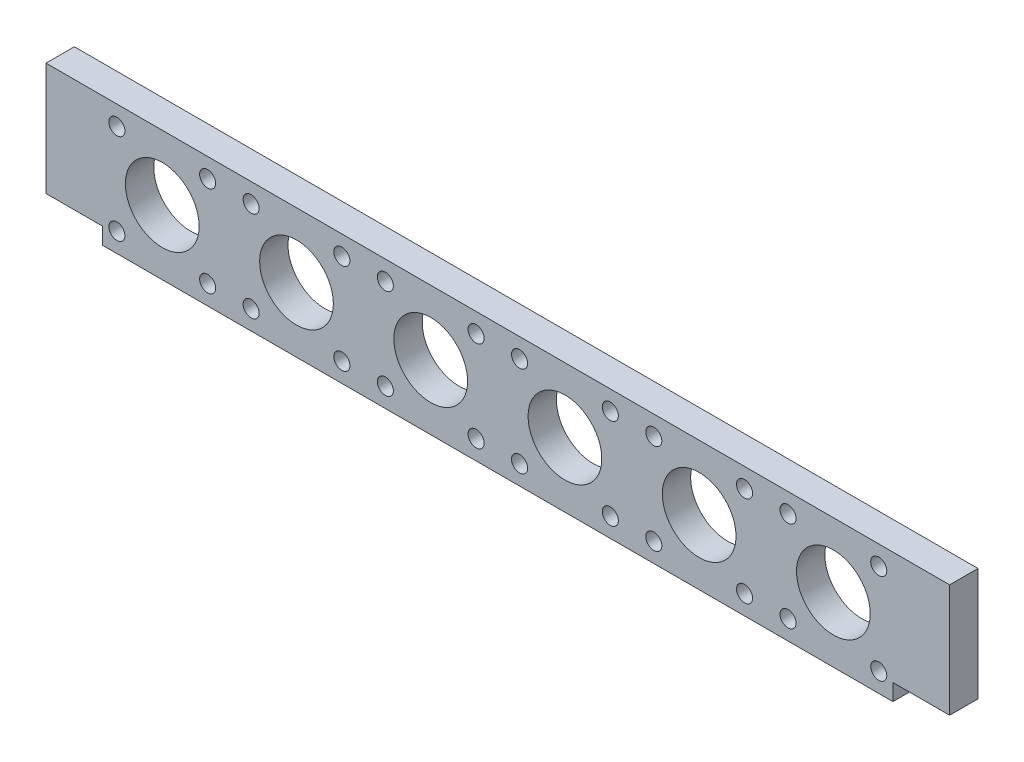
SolidWorks part; units mm, degrees
ref_plane "Front" through (0, 0, 0) normal (0, 0, 1) x (1, 0, 0)
ref_plane "Top" through (0, 0, 0) normal (0, 1, 0) x (1, 0, 0)
ref_plane "Right" through (0, 0, 0) normal (1, 0, 0) x (0, 0, -1)
sketch "Esquisse1" plane through (0, 0, 0) normal (0, 0, 1) x (1, 0, 0)
  line L1 (0, 0) -> (478, 0)
  line L2 (0, 0) -> (0, 68.5)
  line L3 (0, 68.5) -> (478, 68.5)
  line L4 (478, 0) -> (478, 68.5)
  dimension "D1" = 68.5
  dimension "D2" = 478
extrude "Boss.-Extru.1" add sketch "Esquisse1" along normal blind 15
sketch "Esquisse2" plane through (0, 0, 15) normal (0, 0, 1) x (1, 0, 0)
  line L0 (239, 0) -> (239, 68.5) construction
  line L1 (0, 0) -> (478, 0) construction
  line L2 (478, 68.5) -> (0, 68.5) construction
  line L3 (203.5, 68.5) -> (203.5, 34.25) construction
  line L4 (203.5, 34.25) -> (239, 34.25) construction
  line L5 (168, 68.5) -> (168, 0) construction
  line L6 (132.5, 68.5) -> (132.5, 34.25) construction
  line L7 (97, 68.5) -> (97, 0) construction
  line L8 (61.5, 68.5) -> (61.5, 34.25) construction
  line L9 (416.5, 68.5) -> (416.5, 34.25) construction
  line L10 (381, 68.5) -> (381, 0) construction
  line L11 (345.5, 68.5) -> (345.5, 34.25) construction
  line L12 (310, 68.5) -> (310, 0) construction
  line L13 (274.5, 68.5) -> (274.5, 34.25) construction
  circle A0 centre (227.5, 58.25) radius 4.25
  circle A1 centre (227.5, 10.25) radius 4.25
  circle A2 centre (179.5, 10.25) radius 4.25
  circle A3 centre (179.5, 58.25) radius 4.25
  circle A4 centre (156.5, 58.25) radius 4.25
  circle A5 centre (156.5, 10.25) radius 4.25
  circle A6 centre (108.5, 10.25) radius 4.25
  circle A7 centre (108.5, 58.25) radius 4.25
  circle A8 centre (85.5, 58.25) radius 4.25
  circle A9 centre (85.5, 10.25) radius 4.25
  circle A10 centre (37.5, 10.25) radius 4.25
  circle A11 centre (37.5, 58.25) radius 4.25
  circle A12 centre (440.5, 58.25) radius 4.25
  circle A13 centre (440.5, 10.25) radius 4.25
  circle A14 centre (392.5, 10.25) radius 4.25
  circle A15 centre (392.5, 58.25) radius 4.25
  circle A16 centre (369.5, 58.25) radius 4.25
  circle A17 centre (369.5, 10.25) radius 4.25
  circle A18 centre (321.5, 10.25) radius 4.25
  circle A19 centre (321.5, 58.25) radius 4.25
  circle A20 centre (298.5, 58.25) radius 4.25
  circle A21 centre (298.5, 10.25) radius 4.25
  circle A22 centre (250.5, 10.25) radius 4.25
  circle A23 centre (250.5, 58.25) radius 4.25
  dimension "D1" = 48
  dimension "D2" = 48
  dimension "D3" = 8.5
  dimension "D4" = 71
  dimension "D5" = 71
  dimension "D6" = 71
extrude "Enlèv. mat.-Extru.1" cut sketch "Esquisse2" against normal through all both and the other way through all
sketch "Esquisse3" plane through (0, 0, 15) normal (0, 0, 1) x (1, 0, 0)
  line L0 (179.5, 10.25) -> (227.5, 58.25) construction
  line L1 (108.5, 10.25) -> (156.5, 58.25) construction
  line L2 (37.5, 10.25) -> (85.5, 58.25) construction
  line L3 (239, 0) -> (239, 68.5) construction
  line L4 (0, 0) -> (478, 0) construction
  line L5 (478, 68.5) -> (0, 68.5) construction
  line L6 (440.5, 10.25) -> (392.5, 58.25) construction
  line L7 (369.5, 10.25) -> (321.5, 58.25) construction
  line L8 (298.5, 10.25) -> (250.5, 58.25) construction
  circle A0 centre (203.5, 34.25) radius 19.5
  circle A1 centre (132.5, 34.25) radius 19.5
  circle A2 centre (61.5, 34.25) radius 19.5
  circle A3 centre (416.5, 34.25) radius 19.5
  circle A4 centre (345.5, 34.25) radius 19.5
  circle A5 centre (274.5, 34.25) radius 19.5
  dimension "D1" = 39
extrude "Enlèv. mat.-Extru.2" cut sketch "Esquisse3" against normal through all both and the other way through all
sketch "Esquisse4" plane through (0, 0, 15) normal (0, 0, 1) x (1, 0, 0)
  line L0 (239, 0) -> (239, 68.5) construction
  line L1 (0, 0) -> (30, 0)
  line L2 (0, 0) -> (0, 8.75)
  line L3 (0, 8.75) -> (30, 8.75)
  line L4 (30, 0) -> (30, 8.75)
  line L5 (0, 0) -> (478, 0) construction
  line L6 (478, 68.5) -> (0, 68.5) construction
  line L7 (448, 0) -> (448, 8.75)
  line L8 (478, 8.75) -> (448, 8.75)
  line L9 (478, 0) -> (478, 8.75)
  line L10 (478, 0) -> (448, 0)
  dimension "D1" = 8.75
  dimension "D2" = 30
extrude "Enlèv. mat.-Extru.3" cut sketch "Esquisse4" against normal through all both and the other way through all
